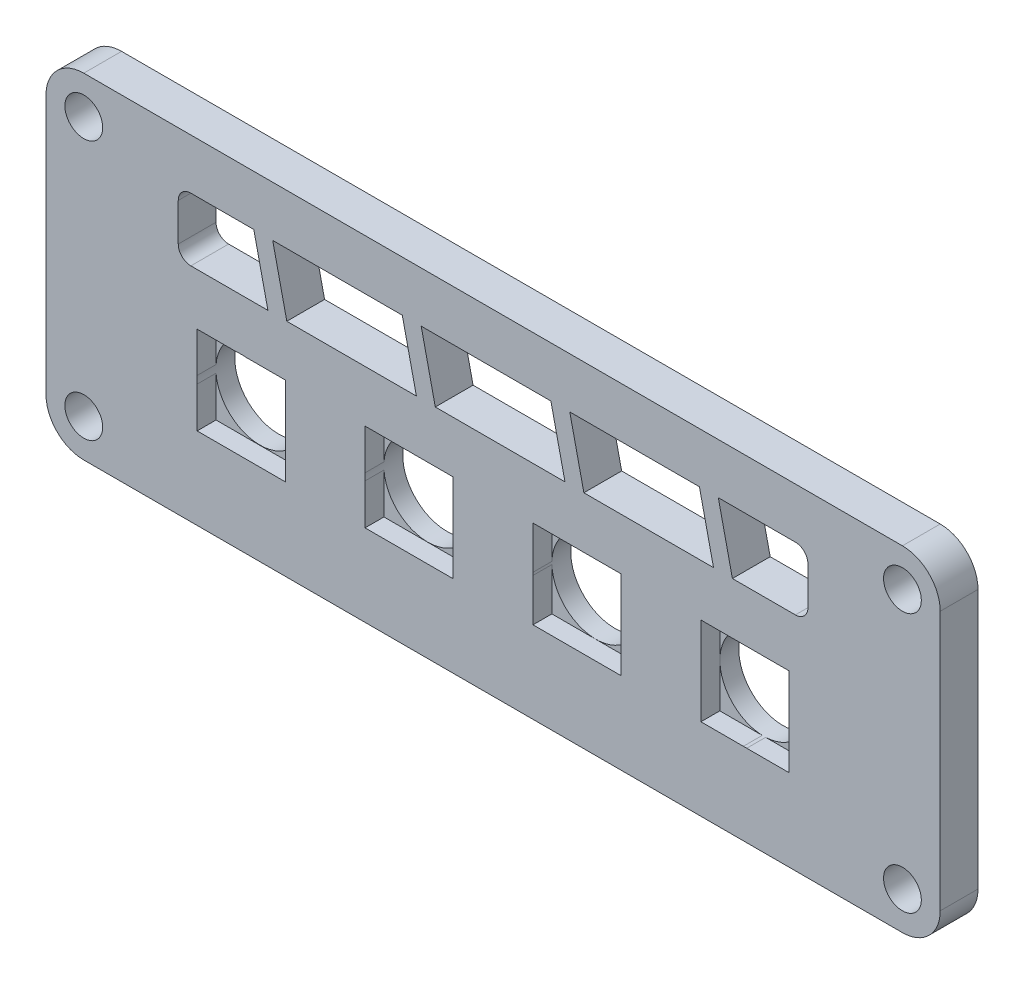
SolidWorks part; units mm, degrees
ref_plane "前视基准面" through (0, 0, 0) normal (0, 0, 1) x (1, 0, 0)
ref_plane "上视基准面" through (0, 0, 0) normal (0, 1, 0) x (1, 0, 0)
ref_plane "右视基准面" through (0, 0, 0) normal (1, 0, 0) x (0, 0, -1)
other "Configuration Table"
sketch "草图1" plane through (0, 0, 0) normal (0, 0, 1) x (1, 0, 0)
  line L1 (3, 0) -> (68, 0)
  line L2 (0, -3) -> (0, -23.6)
  line L3 (3, -26.6) -> (68, -26.6)
  line L4 (71, -3) -> (71, -23.6)
  arc A0 (3, 0) -> (0, -3) centre (3, -3) ccw
  arc A1 (0, -23.6) -> (3, -26.6) centre (3, -23.6) ccw
  arc A2 (68, -26.6) -> (71, -23.6) centre (68, -23.6) ccw
  arc A3 (68, 0) -> (71, -3) centre (68, -3) cw
  circle A4 centre (3, -3) radius 1.5
  circle A5 centre (68, -3) radius 1.5
  circle A6 centre (68, -23.6) radius 1.5
  circle A7 centre (3, -23.6) radius 1.5
  point P7 (0, 0)
  point P12 (71, -26.6)
  point P15 (71, 0)
  dimension "D3" = 3
  dimension "D1" = 71
  dimension "D2" = 26.6
extrude "凸台-拉伸1" add sketch "草图1" along normal blind 3
sketch "草图2" plane through (0, 0, 3) normal (0, 0, 1) x (1, 0, 0)
  line L0 (0, -3) -> (0, -23.6) construction
  line L1 (5.5, -13.1) -> (65.5, -13.1)
  line L2 (5.5, -13.1) -> (5.5, -20.1)
  line L3 (5.5, -20.1) -> (65.5, -20.1)
  line L4 (65.5, -13.1) -> (65.5, -20.1)
  line L5 (3, -26.6) -> (68, -26.6) construction
  line L8 (12, -13.1) -> (19, -13.1)
  line L9 (12, -13.1) -> (12, -20.1)
  line L10 (12, -20.1) -> (19, -20.1)
  line L11 (19, -13.1) -> (19, -20.1)
  line L12 (25.333, -13.1) -> (32.333, -13.1)
  line L13 (25.333, -13.1) -> (25.333, -20.1)
  line L14 (25.333, -20.1) -> (32.333, -20.1)
  line L15 (32.333, -13.1) -> (32.333, -20.1)
  line L16 (38.666, -13.1) -> (45.666, -13.1)
  line L17 (38.666, -13.1) -> (38.666, -20.1)
  line L18 (38.666, -20.1) -> (45.666, -20.1)
  line L19 (45.666, -13.1) -> (45.666, -20.1)
  line L20 (52, -13.1) -> (59, -13.1)
  line L21 (52, -13.1) -> (52, -20.1)
  line L22 (52, -20.1) -> (59, -20.1)
  line L23 (59, -13.1) -> (59, -20.1)
  point P24 (0, 0)
  point P25 (0, 0)
  dimension "D1" = 60
  dimension "D2" = 5.5
  dimension "D3" = 6.5
  dimension "D4" = 13.5
  dimension "D5" = 7
  dimension "D6" = 7
  dimension "D7" = 7
  dimension "D8" = 7
  dimension "D9" = 6.5
  dimension "D10" = 19.833
  dimension "D11" = 33.166
  dimension "D12" = 46.5
extrude "切除-拉伸1" cut sketch "草图2" against normal blind 1.5 contours L11 L1 L9 L3 | L15 L1 L13 L3 | L19 L1 L17 L3 | L23 L1 L21 L3
sketch "草图3" plane through (0, 0, 3) normal (0, 0, 1) x (1, 0, 0)
  circle A0 centre (15.4873, -16.5817) radius 3.5
  circle A1 centre (28.822, -16.5916) radius 3.5
  circle A2 centre (42.1643, -16.5959) radius 3.5
  circle A3 centre (55.5046, -16.6026) radius 3.5
extrude "切除-拉伸2" cut sketch "草图3" against normal blind 3 contours A3 | A2 | A1 | A0
sketch "草图4" plane through (0, 0, 0) normal (0, 0, -1) x (-1, 0, 0)
  line L0 (-71, -23.6) -> (-71, -3) construction
  line L1 (-59.5, -4) -> (-11.5, -4)
  line L2 (-60.5, -5) -> (-60.5, -8)
  line L3 (-59.5, -9) -> (-11.5, -9)
  line L4 (-10.5, -5) -> (-10.5, -8)
  line L5 (-68, 0) -> (-3, 0) construction
  line L6 (-53.3803, -4) -> (-54.5, -9)
  line L7 (-53.3803, -4) -> (-51.8803, -4)
  line L8 (-54.5, -9) -> (-53, -9)
  line L9 (-51.8803, -4) -> (-53, -9)
  line L10 (53.5598, -6.5) -> (52.4402, -11.5)
  line L11 (53.5598, -6.5) -> (55.0598, -6.5)
  line L12 (52.4402, -11.5) -> (53.9402, -11.5)
  line L13 (55.0598, -6.5) -> (53.9402, -11.5)
  line L14 (53.5598, -6.5) -> (52.4402, -11.5)
  line L15 (53.5598, -6.5) -> (55.0598, -6.5)
  line L16 (52.4402, -11.5) -> (53.9402, -11.5)
  line L17 (55.0598, -6.5) -> (53.9402, -11.5)
  line L18 (-18, -4) -> (-19.1197, -9)
  line L19 (-18, -4) -> (-16.5, -4)
  line L20 (-19.1197, -9) -> (-17.6197, -9)
  line L21 (-16.5, -4) -> (-17.6197, -9)
  line L22 (-41.587, -4) -> (-42.7067, -9)
  line L23 (-41.587, -4) -> (-40.087, -4)
  line L24 (-42.7067, -9) -> (-41.2067, -9)
  line L25 (-40.087, -4) -> (-41.2067, -9)
  line L26 (-29.79, -4) -> (-30.9097, -9)
  line L27 (-29.79, -4) -> (-28.29, -4)
  line L28 (-30.9097, -9) -> (-29.4097, -9)
  line L29 (-28.29, -4) -> (-29.4097, -9)
  arc A0 (-11.5, -4) -> (-10.5, -5) centre (-11.5, -5) cw
  arc A1 (-11.5, -9) -> (-10.5, -8) centre (-11.5, -8) ccw
  arc A2 (-60.5, -8) -> (-59.5, -9) centre (-59.5, -8) ccw
  arc A3 (-59.5, -4) -> (-60.5, -5) centre (-59.5, -5) ccw
  point P10 (-10.5, -4)
  point P15 (-60.5, -9)
  point P18 (-60.5, -4)
  point P35 (0, 0)
  point P36 (0, 0)
  dimension "D5" = 1
  dimension "D1" = 50
  dimension "D2" = 10.5
  dimension "D3" = 5
  dimension "D4" = 4
  dimension "D6" = 1.5
  dimension "D7" = 5
  dimension "D8" = 5
  dimension "D9" = 1.5
  dimension "D10" = 1.5
  dimension "D11" = 1.5
  dimension "D12" = 11.7933
  dimension "D13" = 11.79
extrude "切除-拉伸3" cut sketch "草图4" against normal blind 3 contours L22 L1 L9 L3 | L1 A3 L2 A2 L3 L6 | L26 L1 L25 L3 | L1 L29 L3 L18 | L3 A1 L4 A0 L1 L21
